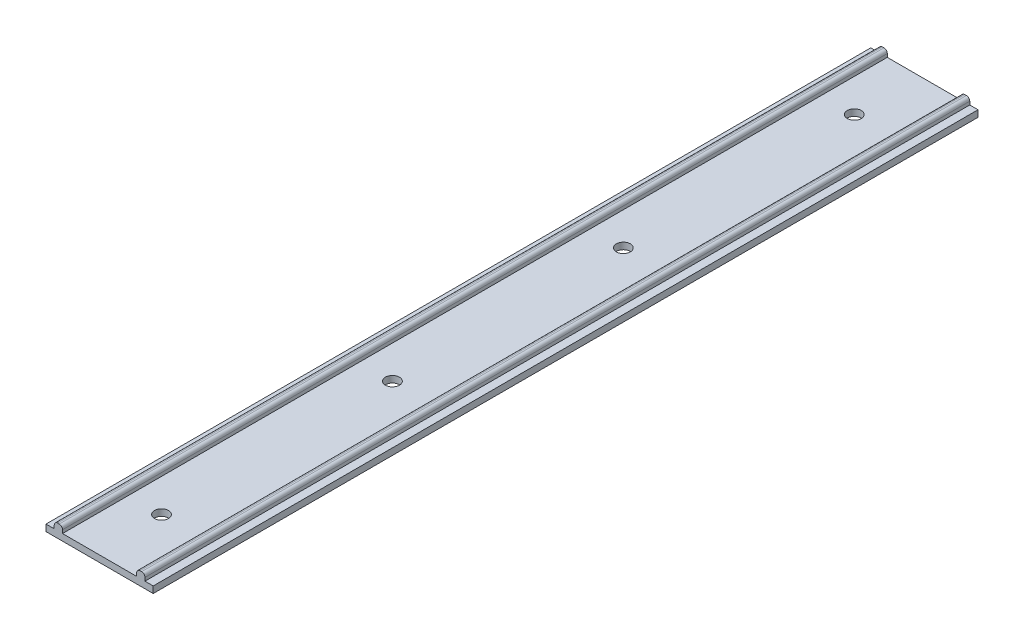
SolidWorks part; units mm, degrees
ref_plane "Ön Düzlem" through (0, 0, 0) normal (0, 0, 1) x (1, 0, 0)
ref_plane "Üst Düzlem" through (0, 0, 0) normal (0, 1, 0) x (1, 0, 0)
ref_plane "Sağ Düzlem" through (0, 0, 0) normal (1, 0, 0) x (0, 0, -1)
sketch "Çizim1" plane through (0, 0, 0) normal (0, 0, 1) x (1, 0, 0)
  line L0 (0, 0) -> (65, 0)
  line L1 (0, 0) -> (0, 4)
  line L2 (0, 4) -> (5, 4)
  line L3 (5, 4) -> (5, 8)
  line L4 (5, 8) -> (10, 8)
  line L5 (10, 8) -> (10, 4)
  line L6 (10, 4) -> (55, 4)
  line L7 (55, 4) -> (55, 8)
  line L8 (55, 8) -> (60, 8)
  line L9 (60, 8) -> (60, 4)
  line L10 (60, 4) -> (65, 4)
  line L11 (65, 4) -> (65, 0)
  dimension "D1" = 5
  dimension "D2" = 45
  dimension "D3" = 5
  dimension "D4" = 5
  dimension "D5" = 5
  dimension "D6" = 8
  dimension "D7" = 4
extrude "Yükseklik-Ekstrüzyon1" add sketch "Çizim1" against normal blind 500
fillet "Radyus1" radius 2 4 edges at (60, 8, -250) (55, 8, -250) (10, 8, -250) (5, 8, -250)
sketch "Çizim2" plane through (0, 0, 0) normal (0, -1, 0) x (1, 0, 0)
  line L0 (0, 0) -> (65, 0) construction
  line L1 (0, -500) -> (65, -500) construction
  line L2 (0, -500) -> (0, 0) construction
  circle A0 centre (30, -40) radius 4.25
  circle A1 centre (30, -180) radius 4.25
  circle A2 centre (30, -320) radius 4.25
  circle A3 centre (30, -460) radius 4.25
  dimension "D1" = 8.5
  dimension "D2" = 40
  dimension "D4" = 140
  dimension "D5" = 140
  dimension "D6" = 30
  dimension "D3" = 40
extrude "Kes-Ekstrüzyon1" cut sketch "Çizim2" against normal blind 10
